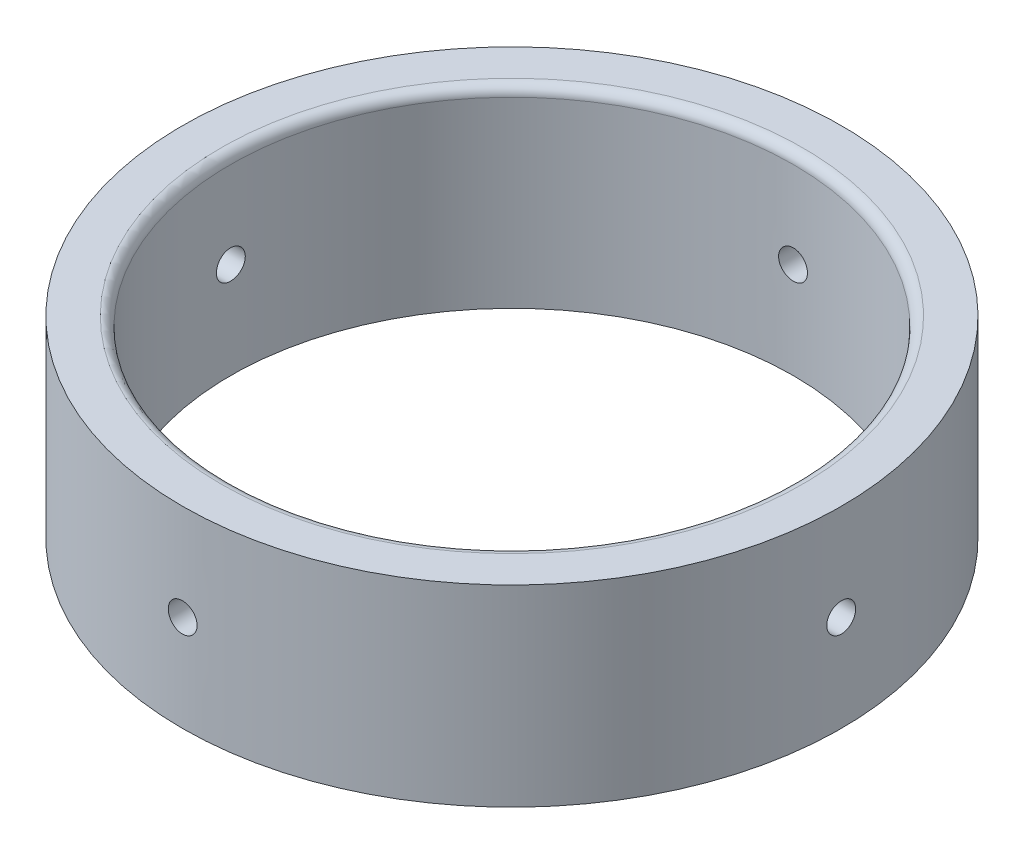
SolidWorks part; units mm, degrees
ref_plane "Front Plane" through (0, 0, 0) normal (0, 0, 1) x (1, 0, 0)
ref_plane "Top Plane" through (0, 0, 0) normal (0, 1, 0) x (1, 0, 0)
ref_plane "Right Plane" through (0, 0, 0) normal (1, 0, 0) x (0, 0, -1)
sketch "Sketch1" plane through (0, 0, 0) normal (0, 1, 0) x (1, 0, 0)
  circle A0 centre (0, 0) radius 29.25
  circle A1 centre (0, 0) radius 34.25
  dimension "D1" = 58.5
  dimension "D2" = 5
extrude "Boss-Extrude1" add sketch "Sketch1" along normal blind 20
ref_plane "Plane1" through (-34.25, 0, 0) normal (-1, 0, 0) x (0, 0, 1)
sketch "Sketch2" plane through (-34.25, 0, 0) normal (-1, 0, 0) x (0, 0, 1)
  line L0 (0, 20) -> (0, 0) construction
  line L1 (34.25, 20) -> (-34.25, 20) construction
  circle A0 centre (0, 10) radius 1.5
  dimension "D1" = 3
extrude "Cut-Extrude1" cut sketch "Sketch2" against normal blind 20
ref_axis "Axis1" through (0, 20, 0) along (0, -1, 0)
pattern_circular "CirPattern1" count 4 over 360 about axis through (0, 20, 0) along (0, -1, 0) of "Cut-Extrude1"
fillet "Fillet1" radius 1 1 edges at (0, 20, 29.25)
